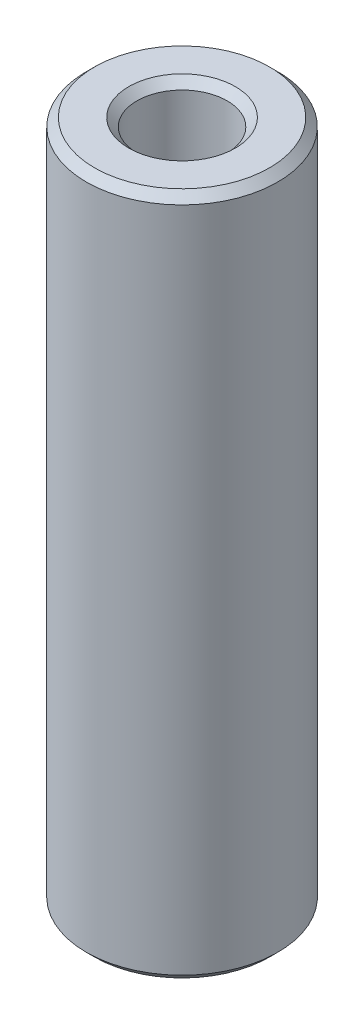
SolidWorks part; units mm, degrees
ref_plane "정면" through (0, 0, 0) normal (0, 0, 1) x (1, 0, 0)
ref_plane "윗면" through (0, 0, 0) normal (0, 1, 0) x (1, 0, 0)
ref_plane "우측면" through (0, 0, 0) normal (1, 0, 0) x (0, 0, -1)
sketch "스케치1" plane through (0, 0, 0) normal (0, 1, 0) x (1, 0, 0)
  circle A0 centre (0, 0) radius 3.5
  circle A1 centre (0, 0) radius 1.65
  dimension "D1" = 3.3
  dimension "D2" = 7
extrude "보스-돌출1" add sketch "스케치1" along normal blind 25 contours A1 | A0 A1
hole_wizard "M4 탭을 위한 탭 드릴1" positions "스케치2" profile "스케치3" hole size "M4" standard "ISO"
sketch "스케치2" plane through (0, 0, 0) normal (0, -1, 0) x (-1, 0, 0)
  point P0 (0, 0)
sketch "스케치3" plane through (0, 0, 0) normal (1, 0, 0) x (0, 0, -1)
  line L0 (0, 0) -> (0, 10.9914)
  line L1 (0, 10.9914) -> (1.65, 10)
  line L2 (1.65, 10) -> (1.65, 0)
  line L5 (1.65, 0) -> (0, 0)
  line L10 (0, 10.9914) -> (-1.65, 10) construction
  line L11 (0, -6.35) -> (0, 107.95) construction
  dimension "구멍 지름" = 3.3
  dimension "구멍 깊이" = 10
  dimension "드릴 각도" = 118
hole_wizard "M4 탭을 위한 탭 드릴2" positions "스케치4" profile "스케치5" hole size "M4" standard "ISO"
sketch "스케치4" plane through (0, 25, 0) normal (0, 1, 0) x (1, 0, 0)
  point P0 (0, 0)
sketch "스케치5" plane through (0, 25, 0) normal (1, 0, 0) x (0, 0, 1)
  line L0 (0, 0) -> (0, 10.9914)
  line L1 (0, 10.9914) -> (1.65, 10)
  line L2 (1.65, 10) -> (1.65, 0)
  line L5 (1.65, 0) -> (0, 0)
  line L10 (0, 10.9914) -> (-1.65, 10) construction
  line L11 (0, -6.35) -> (0, 107.95) construction
  dimension "구멍 지름" = 3.3
  dimension "구멍 깊이" = 10
  dimension "드릴 각도" = 118
chamfer "모따기1" distance 0.3 angle 45 4 edges at (0, 0, 3.5) (0, 0, -1.65) (0, 25, 3.5) (0, 25, 1.65)
